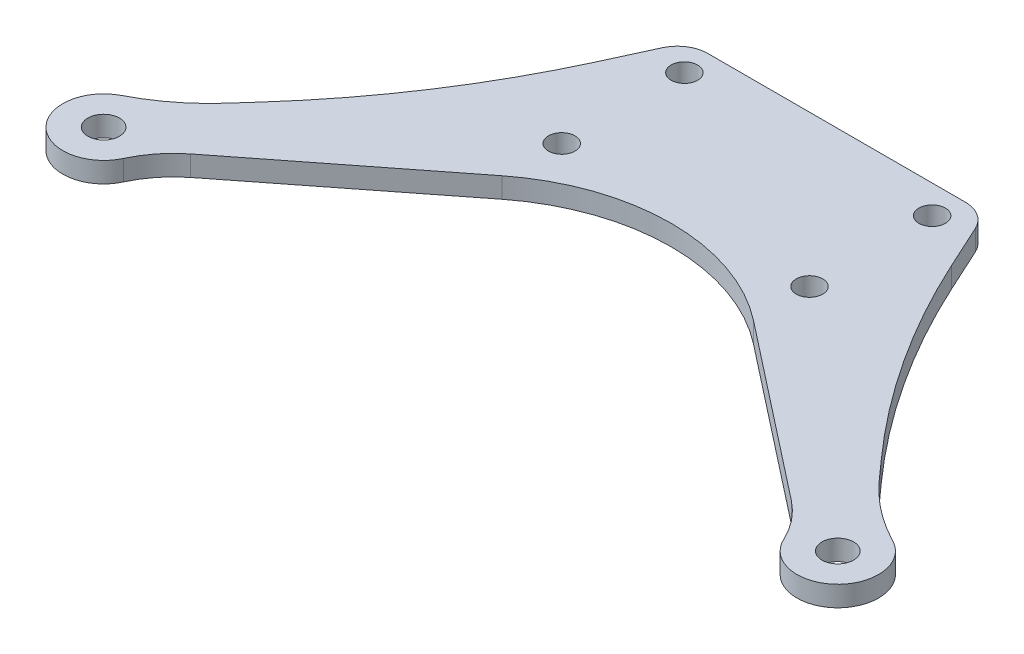
SolidWorks part; units mm, degrees
ref_plane "前视基准面" through (0, 0, 0) normal (0, 0, 1) x (1, 0, 0)
ref_plane "上视基准面" through (0, 0, 0) normal (0, 1, 0) x (1, 0, 0)
ref_plane "右视基准面" through (0, 0, 0) normal (1, 0, 0) x (0, 0, -1)
sketch "草图1" plane through (0, 0, 0) normal (0, 1, 0) x (1, 0, 0)
  line L5 (42, -50) -> (-37.6187, 44.7842) construction
  line L6 (42, 50) -> (38.6424, 46.0029) construction
  line L11 (-36, -43) -> (36, 43) construction
  line L12 (-36, 43) -> (36, -43) construction
  line L17 (-48, -77.1001) -> (36.8783, 59.2358) construction
  line L18 (-32.0373, 51.0287) -> (-30.4025, 52.8577)
  line L23 (12.6234, 78.8853) -> (-12.6234, 78.8853)
  line L26 (-29.4648, 44.9866) -> (-12.3359, 58.409)
  line L27 (12.3359, 58.409) -> (29.4648, 44.9866)
  line L35 (-15.3497, 77.1372) -> (-17.348, 72.7857)
  line L36 (0, 86.7256) -> (0, 20.02) construction
  line L37 (15.3497, 77.1372) -> (17.348, 72.7857)
  line L39 (-31.879, 51.2058) -> (48, -77.1001) construction
  line L40 (32.0373, 51.0287) -> (30.4025, 52.8577)
  line L41 (37.6187, 44.7842) -> (-42, -50) construction
  circle A2 centre (36, 43) radius 1.55
  circle A3 centre (-36, 43) radius 1.55
  circle A8 centre (-12.15, 76.1055) radius 1.3
  circle A9 centre (12.15, 76.1055) radius 1.3
  circle A10 centre (-12.15, 64.0755) radius 1.3
  circle A11 centre (12.15, 64.0755) radius 1.3
  arc A13 (-39.9209, 42.2085) -> (-32.3705, 41.3187) centre (-36, 43) ccw
  arc A15 (32.3705, 41.3187) -> (39.9209, 42.2085) centre (36, 43) ccw
  arc A23 (29.4648, 44.9866) -> (32.3705, 41.3187) centre (23.2968, 37.1154) cw
  arc A24 (-29.4648, 44.9866) -> (-32.3705, 41.3187) centre (-23.2968, 37.1154) ccw
  arc A30 (-12.3359, 58.409) -> (12.3359, 58.409) centre (0, 42.6665) cw
  arc A41 (-37.8248, 46.5595) -> (-32.3705, 41.3187) centre (-36, 43) ccw
  arc A42 (32.3705, 41.3187) -> (37.8248, 46.5595) centre (36, 43) ccw
  arc A43 (12.6234, 78.8853) -> (15.3497, 77.1372) centre (12.6234, 75.8853) cw
  arc A44 (-12.6234, 78.8853) -> (-15.3497, 77.1372) centre (-12.6234, 75.8853) ccw
  arc A45 (37.8248, 46.5595) -> (32.0373, 51.0287) centre (46.9489, 64.357) cw
  arc A46 (-32.0373, 51.0287) -> (-37.8248, 46.5595) centre (-46.9489, 64.357) cw
  arc A47 (17.348, 72.7857) -> (30.4025, 52.8577) centre (90.0489, 106.1709) ccw
  arc A48 (-17.348, 72.7857) -> (-30.4025, 52.8577) centre (-90.0489, 106.1709) cw
  point P0 (0, 0)
  point P6 (0, 0)
  point P15 (0, 0)
  point P21 (14.547, 78.8853)
  point P23 (42, 54)
  point P36 (32, 43)
  point P40 (-14.547, 78.8853)
  point P43 (-32, 43)
  point P53 (22.3749, 61.8389)
  point P54 (19.241, 76.1055)
  point P55 (-42, 54)
  point P58 (40, 43)
  point P61 (42, 46)
  point P62 (-22.3749, 61.8389)
  point P64 (-40, 43)
  point P67 (-42, 46)
  point P72 (20.5907, 76.1055)
  point P73 (-19.241, 76.1055)
  point P75 (-20.5907, 76.1055)
  point P85 (-29.9094, 48.042)
  dimension "D1" = 3
  dimension "D2" = 20
  dimension "D3" = 20
  dimension "D4" = 80
  dimension "D5" = 72
extrude "凸台-拉伸1" add sketch "草图1" along normal blind 2
